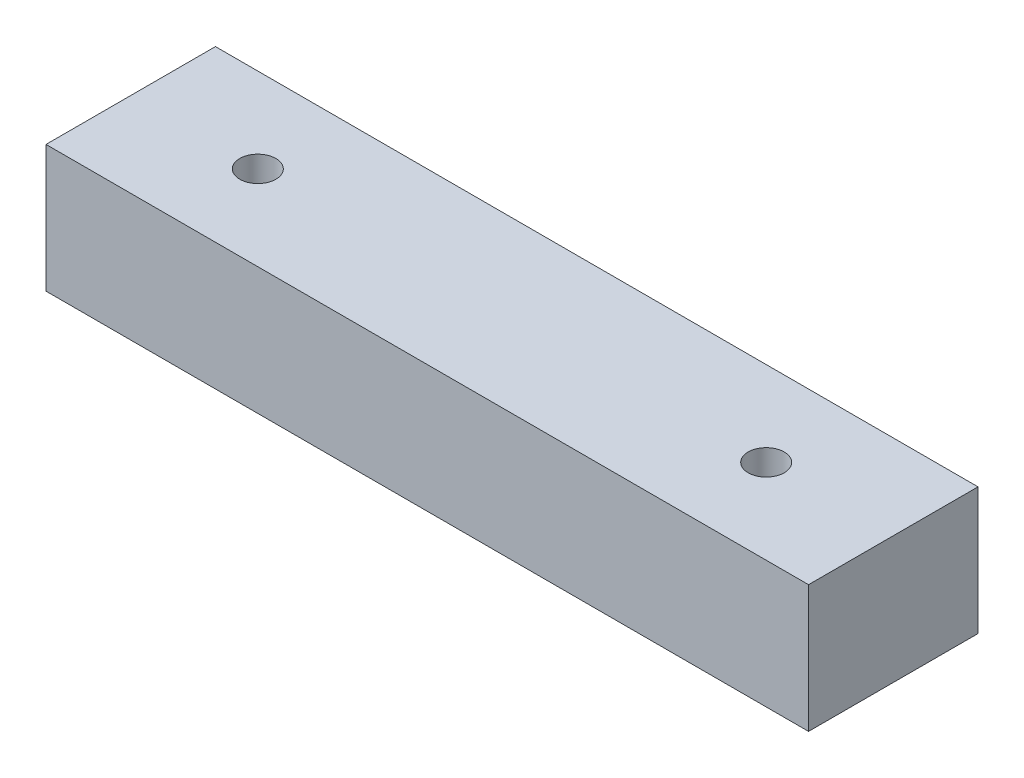
SolidWorks part; units mm, degrees
material "6061 Alloy"
ref_plane "Front Plane" through (0, 0, 0) normal (0, 0, 1) x (1, 0, 0)
ref_plane "Top Plane" through (0, 0, 0) normal (0, 1, 0) x (1, 0, 0)
ref_plane "Right Plane" through (0, 0, 0) normal (1, 0, 0) x (0, 0, -1)
sketch "Sketch1" plane through (0, 0, 0) normal (0, 1, 0) x (1, 0, 0)
  line L1 (28.575, -6.35) -> (-28.575, -6.35)
  line L2 (28.575, -6.35) -> (28.575, 6.35)
  line L3 (28.575, 6.35) -> (-28.575, 6.35)
  line L4 (-28.575, -6.35) -> (-28.575, 6.35)
  line L5 (28.575, -6.35) -> (-28.575, 6.35) construction
  line L6 (28.575, 6.35) -> (-28.575, -6.35) construction
  point P0 (0, 0)
  dimension "D1" = 57.15
  dimension "D2" = 12.7
extrude "Boss-Extrude1" add sketch "Sketch1" along normal blind 9.525
hole_wizard "#6-32 Tapped Hole1" positions "Sketch3" profile "Sketch4" tap size "#6-32" standard "Ansi Inch" end condition through all
sketch "Sketch3" plane through (0, 0, 0) normal (0, -1, 0) x (1, 0, 0)
  point P1 (19.05, 0)
  point P4 (-19.05, 0)
  dimension "D1" = 38.1
  dimension "D2" = 19.05
sketch "Sketch4" plane through (19.05, 0, 0) normal (1, 0, 0) x (0, 0, -1)
  line L0 (0, 0) -> (0, 9.525)
  line L1 (0, 9.525) -> (1.3525, 9.525)
  line L2 (1.3525, 9.525) -> (1.3525, 0)
  line L5 (1.3525, 0) -> (0, 0)
  line L11 (0, -6.35) -> (0, 107.95) construction
  dimension "Thru Tap Drill Dia." = 2.7051
  dimension "Thru Tap Drill Depth" = 9.525
cosmetic thread "Hole Thread1"
cosmetic thread "Hole Thread2"
equation "\"D2@Sketch3\" = \"D1@Sketch3\"/2"
